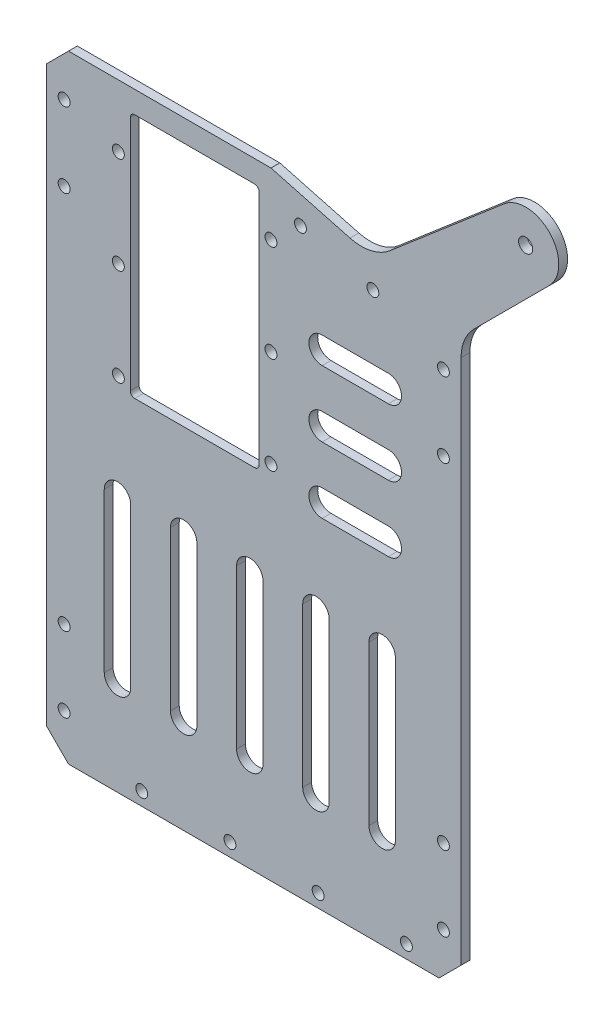
SolidWorks part; units mm, degrees
ref_plane "前视基准面" through (0, 0, 0) normal (0, 0, 1) x (1, 0, 0)
ref_plane "上视基准面" through (0, 0, 0) normal (0, 1, 0) x (1, 0, 0)
ref_plane "右视基准面" through (0, 0, 0) normal (1, 0, 0) x (0, 0, -1)
sketch "草图1" plane through (0, 0, 0) normal (0, 0, 1) x (1, 0, 0)
  line L0 (0, 49.9422) -> (0, -59.0303) construction
  line L1 (-46.1, 41.8134) -> (7.9, 41.8134)
  line L2 (47.9, 41.8134) -> (47.9, -98.1866)
  line L3 (-46.1, -98.1866) -> (47.9, -98.1866)
  line L4 (-46.1, 41.8134) -> (-46.1, -98.1866)
  line L5 (-12.5, 41.0614) -> (-12.5, -107.263) construction
  line L7 (47.9, 41.8134) -> (7.9, 41.8134)
  line L8 (-27.1, 36.8134) -> (2.1, 36.8134)
  line L9 (-17, 24.7134) -> (17, 24.7134) construction
  line L10 (-27.1, 36.8134) -> (-27.1, -18.8866)
  line L11 (-27.1, -18.8866) -> (2.1, -18.8866)
  line L12 (2.1, 36.8134) -> (2.1, -18.8866)
  line L14 (5.5, -79.2172) -> (5.5, -94.4316) construction
  circle A0 centre (-4.5, -95.1866) radius 1.35
  circle A1 centre (-24.5, -95.1866) radius 1.35
  circle A2 centre (35.5, -95.1866) radius 1.35
  circle A3 centre (-29.8, 5.7134) radius 1.35
  circle A4 centre (-29.8, -16.2866) radius 1.35
  circle A5 centre (4.8, -16.2866) radius 1.35
  circle A6 centre (4.8, 5.7134) radius 1.35
  circle A7 centre (4.8, 27.7134) radius 1.35
  circle A8 centre (-29.8, 27.7134) radius 1.35
  circle A9 centre (15.5, -95.1866) radius 1.35
  point P0 (0, 0)
  point P2 (-12.5, 24.7134)
  dimension "D6" = 29.2
  dimension "D10" = 12.1
  dimension "D18" = 3
  dimension "D13" = 2.7
  dimension "D14" = 3
  dimension "D17" = 5
  dimension "D4" = 10
  dimension "D5" = 2.7
  dimension "D3" = 18
  dimension "D7" = 14.6
  dimension "D8" = 55.7
  dimension "D9" = 33.6
  dimension "D11" = 17.3
  dimension "D12" = 9.1
  dimension "D15" = 54
  dimension "D16" = 140
  dimension "D20" = 20
  dimension "D22" = 40
extrude "凸台-拉伸1" add sketch "草图1" along normal blind 2
fillet "圆角1" radius 1 4 edges at (-27.1, -18.8866, 1) (2.1, -18.8866, 1) (2.1, 36.8134, 1) (-27.1, 36.8134, 1)
sketch "草图2" plane through (0, 0, 2) normal (0, 0, 1) x (1, 0, 0)
  line L0 (-76.0217, -28.1866) -> (54.1424, -28.1866) construction
  line L1 (-46.1, -98.1866) -> (47.9, -98.1866) construction
  line L2 (-46.1, 41.8134) -> (-46.1, -98.1866) construction
  line L3 (47.9, -98.1866) -> (47.9, 41.8134) construction
  circle A0 centre (-42.1, 31.8134) radius 1.35
  circle A2 centre (-42.1, 14.8134) radius 1.35
  circle A3 centre (-42.1, -71.1866) radius 1.35
  circle A4 centre (-42.1, -88.1866) radius 1.35
  circle A5 centre (43.9, -88.1866) radius 1.35
  circle A6 centre (43.9, -71.1866) radius 1.35
  circle A7 centre (43.9, 21.8134) radius 1.35
  circle A8 centre (43.9, 4.8134) radius 1.35
  dimension "D2" = 2.7
  dimension "D6" = 17
  dimension "D7" = 2.7
  dimension "D11" = 2.7
  dimension "D1" = 70
  dimension "D3" = 4
  dimension "D4" = 17
  dimension "D5" = 60
  dimension "D8" = 4
  dimension "D9" = 60
  dimension "D10" = 17
  dimension "D12" = 4
  dimension "D13" = 33
extrude "切除-拉伸2" cut sketch "草图2" against normal up to next
sketch "草图3" plane through (0, 0, 2) normal (0, 0, 1) x (1, 0, 0)
  line L0 (-46.1, -98.1866) -> (47.9, -98.1866) construction
  line L1 (-3, -40.1866) -> (3, -40.1866) construction
  line L2 (-3, -40.1866) -> (-3, -76.1866)
  line L3 (-3, -76.1866) -> (3, -76.1866) construction
  line L4 (3, -40.1866) -> (3, -76.1866)
  line L5 (-3, -40.1866) -> (3, -76.1866) construction
  line L6 (-3, -76.1866) -> (3, -40.1866) construction
  line L7 (12, -40.1866) -> (12, -76.1866)
  line L8 (18, -40.1866) -> (18, -76.1866)
  line L9 (12, -40.1866) -> (18, -40.1866) construction
  line L10 (12, -76.1866) -> (18, -76.1866) construction
  line L11 (12, -40.1866) -> (18, -76.1866) construction
  line L12 (12, -76.1866) -> (18, -40.1866) construction
  line L13 (27, -40.1866) -> (27, -76.1866)
  line L14 (33, -40.1866) -> (33, -76.1866)
  line L15 (27, -40.1866) -> (33, -40.1866) construction
  line L16 (27, -76.1866) -> (33, -76.1866) construction
  line L17 (27, -40.1866) -> (33, -76.1866) construction
  line L18 (27, -76.1866) -> (33, -40.1866) construction
  line L19 (-18, -40.1866) -> (-18, -76.1866)
  line L20 (-12, -40.1866) -> (-12, -76.1866)
  line L21 (-18, -40.1866) -> (-12, -40.1866) construction
  line L22 (-18, -76.1866) -> (-12, -76.1866) construction
  line L23 (-18, -40.1866) -> (-12, -76.1866) construction
  line L24 (-18, -76.1866) -> (-12, -40.1866) construction
  line L25 (-33, -40.1866) -> (-33, -76.1866)
  line L26 (-27, -40.1866) -> (-27, -76.1866)
  line L27 (-33, -40.1866) -> (-27, -40.1866) construction
  line L28 (-33, -76.1866) -> (-27, -76.1866) construction
  line L29 (-33, -40.1866) -> (-27, -76.1866) construction
  line L30 (-33, -76.1866) -> (-27, -40.1866) construction
  line L31 (47.9, -98.1866) -> (47.9, 41.8134) construction
  line L32 (16.4, -15.1866) -> (31.4, -15.1866)
  line L33 (16.4, -15.1866) -> (16.4, -21.1866) construction
  line L34 (16.4, -21.1866) -> (31.4, -21.1866)
  line L35 (31.4, -15.1866) -> (31.4, -21.1866) construction
  line L36 (16.4, -15.1866) -> (31.4, -21.1866) construction
  line L37 (16.4, -21.1866) -> (31.4, -15.1866) construction
  line L38 (16.4, -0.1866) -> (31.4, -0.1866)
  line L39 (16.4, -6.1866) -> (31.4, -6.1866)
  line L40 (16.4, -0.1866) -> (16.4, -6.1866) construction
  line L41 (31.4, -0.1866) -> (31.4, -6.1866) construction
  line L42 (16.4, -0.1866) -> (31.4, -6.1866) construction
  line L43 (16.4, -6.1866) -> (31.4, -0.1866) construction
  line L44 (16.4, 14.8134) -> (31.4, 14.8134)
  line L45 (16.4, 8.8134) -> (31.4, 8.8134)
  line L46 (16.4, 14.8134) -> (16.4, 8.8134) construction
  line L47 (31.4, 14.8134) -> (31.4, 8.8134) construction
  line L48 (16.4, 14.8134) -> (31.4, 8.8134) construction
  line L49 (16.4, 8.8134) -> (31.4, 14.8134) construction
  arc A0 (3, -40.1866) -> (-3, -40.1866) centre (0, -40.1866) ccw
  arc A1 (-3, -76.1866) -> (3, -76.1866) centre (0, -76.1866) ccw
  arc A2 (18, -40.1866) -> (12, -40.1866) centre (15, -40.1866) ccw
  arc A3 (12, -76.1866) -> (18, -76.1866) centre (15, -76.1866) ccw
  arc A4 (33, -40.1866) -> (27, -40.1866) centre (30, -40.1866) ccw
  arc A5 (27, -76.1866) -> (33, -76.1866) centre (30, -76.1866) ccw
  arc A6 (-12, -40.1866) -> (-18, -40.1866) centre (-15, -40.1866) ccw
  arc A7 (-18, -76.1866) -> (-12, -76.1866) centre (-15, -76.1866) ccw
  arc A8 (-27, -40.1866) -> (-33, -40.1866) centre (-30, -40.1866) ccw
  arc A9 (-33, -76.1866) -> (-27, -76.1866) centre (-30, -76.1866) ccw
  arc A10 (16.4, -21.1866) -> (16.4, -15.1866) centre (16.4, -18.1866) cw
  arc A11 (31.4, -21.1866) -> (31.4, -15.1866) centre (31.4, -18.1866) ccw
  arc A12 (16.4, -6.1866) -> (16.4, -0.1866) centre (16.4, -3.1866) cw
  arc A13 (31.4, -6.1866) -> (31.4, -0.1866) centre (31.4, -3.1866) ccw
  arc A14 (16.4, 8.8134) -> (16.4, 14.8134) centre (16.4, 11.8134) cw
  arc A15 (31.4, 8.8134) -> (31.4, 14.8134) centre (31.4, 11.8134) ccw
  point P0 (0, -58.1866)
  point P9 (23.9, -18.1866)
  point P12 (15, -58.1866)
  point P19 (30, -58.1866)
  point P26 (-15, -58.1866)
  point P33 (-30, -58.1866)
  point P49 (23.9, -3.1866)
  point P56 (23.9, 11.8134)
  dimension "D1" = 6
  dimension "D2" = 36
  dimension "D3" = 40
  dimension "D4" = 3
  dimension "D6" = 6
  dimension "D7" = 15
  dimension "D8" = 24
  dimension "D9" = 80
  dimension "D5" = 3
  dimension "D10" = 3
extrude "切除-拉伸3" cut sketch "草图3" against normal up to next
chamfer "倒角1" distance 5 angle 45 3 edges at (47.9, -98.1866, 1) (-46.1, -98.1866, 1) (-46.1, 41.8134, 1)
sketch "草图4" plane through (0, 0, 2) normal (0, 0, 1) x (1, 0, 0)
  line L5 (9.3523, 34.3833) -> (33.1797, 27.9988) construction
  line L6 (47.9, 41.8134) -> (-41.1, 41.8134) construction
  line L7 (47.9, -93.1866) -> (47.9, 41.8134) construction
  line L8 (3.0008, 42.2968) -> (53.433, 28.7836)
  line L9 (3.0008, 42.2968) -> (46.4051, 52.8165)
  line L10 (46.4051, 52.8165) -> (53.433, 28.7836)
  circle A1 centre (11.4793, 33.8134) radius 1.35
  circle A2 centre (27.9, 29.4134) radius 1.35
  dimension "D3" = 2.7
  dimension "D1" = 15
  dimension "D2" = 17
  dimension "D4" = 8
  dimension "D5" = 20
  dimension "D6" = 6
extrude "切除-拉伸4" cut sketch "草图4" against normal up to next
sketch "草图5" plane through (0, 0, 2) normal (0, 0, 1) x (1, 0, 0)
  line L7 (47.9, 30.2661) -> (67.8518, 50.2179)
  line L8 (4.8051, 41.8134) -> (47.9, 30.2661) construction
  line L9 (27.7983, 35.6523) -> (57.6719, 61.2193)
  line L10 (27.7983, 35.6523) -> (25.8554, 33.0048)
  line L11 (25.8554, 33.0048) -> (41.8313, 29.3283)
  line L12 (41.8313, 29.3283) -> (47.9, 30.2661)
  line L13 (47.9, -93.1866) -> (47.9, 30.2661) construction
  arc A2 (67.8518, 50.2179) -> (57.6719, 61.2193) centre (62.5485, 55.5212) ccw
  circle A3 centre (62.5485, 55.5212) radius 1.6
  point P1 (0, 0)
  dimension "D1" = 15
  dimension "D2" = 3.2
  dimension "D3" = 135
extrude "凸台-拉伸2" add sketch "草图5" against normal blind 2
fillet "圆角3" radius 10 2 edges at (47.9, 30.2661, 1) (27.7983, 35.6523, 1)
